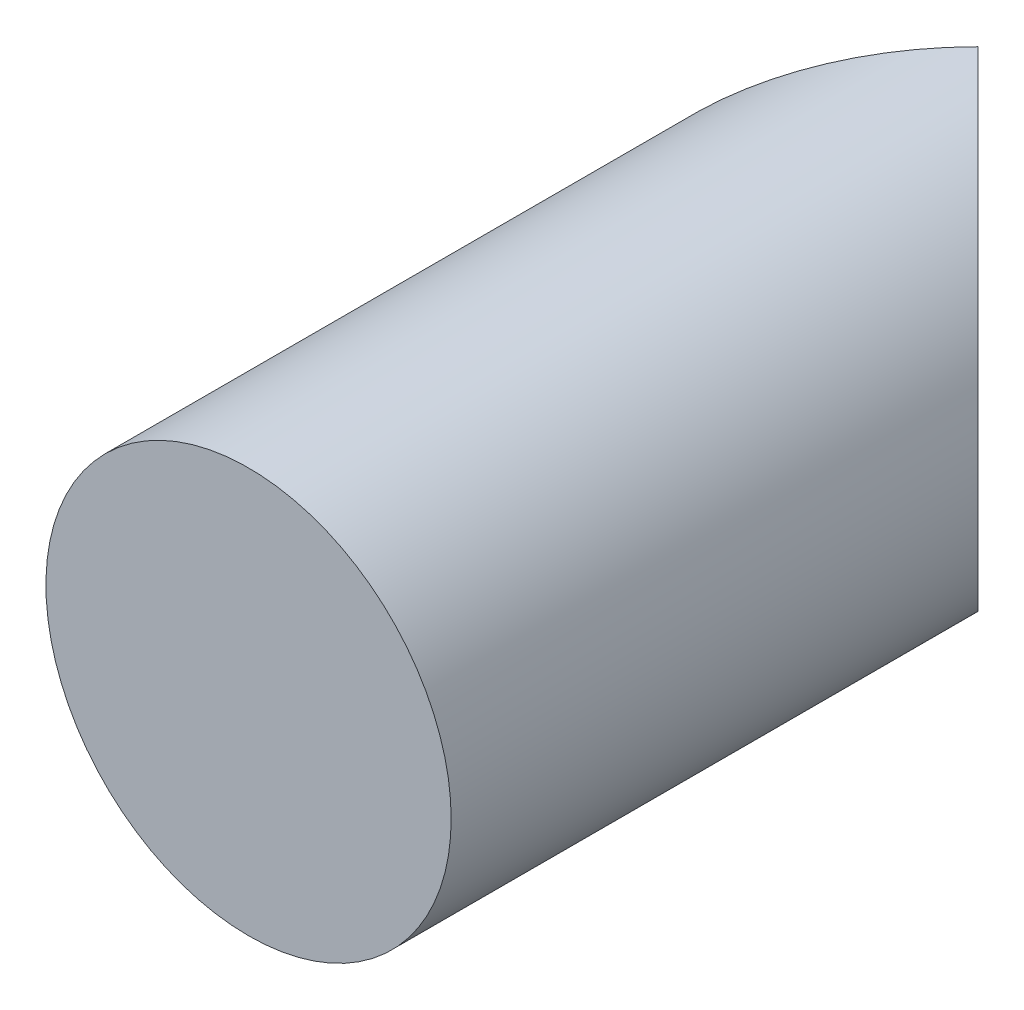
SolidWorks part; units mm, degrees
ref_plane "Front Plane" through (0, 0, 0) normal (0, 0, 1) x (1, 0, 0)
ref_plane "Top Plane" through (0, 0, 0) normal (0, 1, 0) x (1, 0, 0)
ref_plane "Right Plane" through (0, 0, 0) normal (1, 0, 0) x (0, 0, -1)
sketch "Sketch1" plane through (0, 0, 0) normal (0, 0, 1) x (1, 0, 0)
  circle A0 centre (0, 0) radius 12.5
extrude "Boss-Extrude1" add sketch "Sketch1" along normal blind 45
ref_plane "Plane1" through (0, -15.9871, 0) normal (0, -1, 0) x (-1, 0, 0)
sketch "Sketch2" plane through (0, -15.9871, 0) normal (0, -1, 0) x (-1, 0, 0)
  line L0 (0, 0) -> (12.5, 12.5)
  line L1 (12.5, -45) -> (12.5, 0) construction
  line L2 (0, 0) -> (-12.5, 12.5)
  line L3 (-12.5, 0) -> (-12.5, -45) construction
  line L4 (12.5, 12.5) -> (12.5, -12.5)
  line L5 (12.5, 0) -> (-12.5, 0)
  line L6 (-12.5, -12.5) -> (-12.5, 12.5)
  line L7 (0, 0) -> (-12.5, -12.5)
  line L8 (0, 0) -> (12.5, -12.5)
  dimension "D1" = 12.5
  dimension "D2" = 90
extrude "Cut-Extrude6" cut sketch "Sketch2" against normal blind 36 contours L7 L5 L6 | L5 L8 L4
